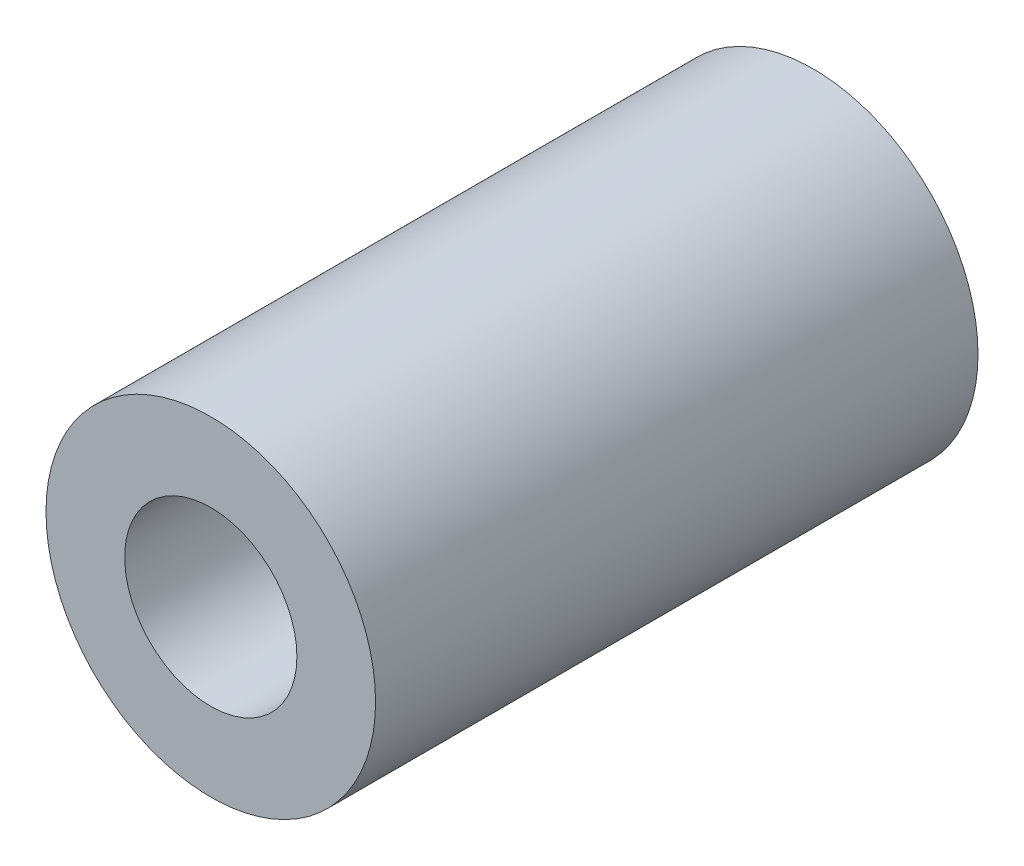
SolidWorks part; units mm, degrees
ref_plane "Front Plane" through (0, 0, 0) normal (0, 0, 1) x (1, 0, 0)
ref_plane "Top Plane" through (0, 0, 0) normal (0, 1, 0) x (1, 0, 0)
ref_plane "Right Plane" through (0, 0, 0) normal (1, 0, 0) x (0, 0, -1)
sketch "Sketch2" plane through (0, 0, 0) normal (0, 0, 1) x (1, 0, 0)
  circle A0 centre (0, 0) radius 4.7625
  circle A1 centre (0, 0) radius 2.4892
  dimension "D1" = 4.9784
  dimension "D2" = 9.525
extrude "Boss-Extrude1" add sketch "Sketch2" along normal mid plane 17.4117
